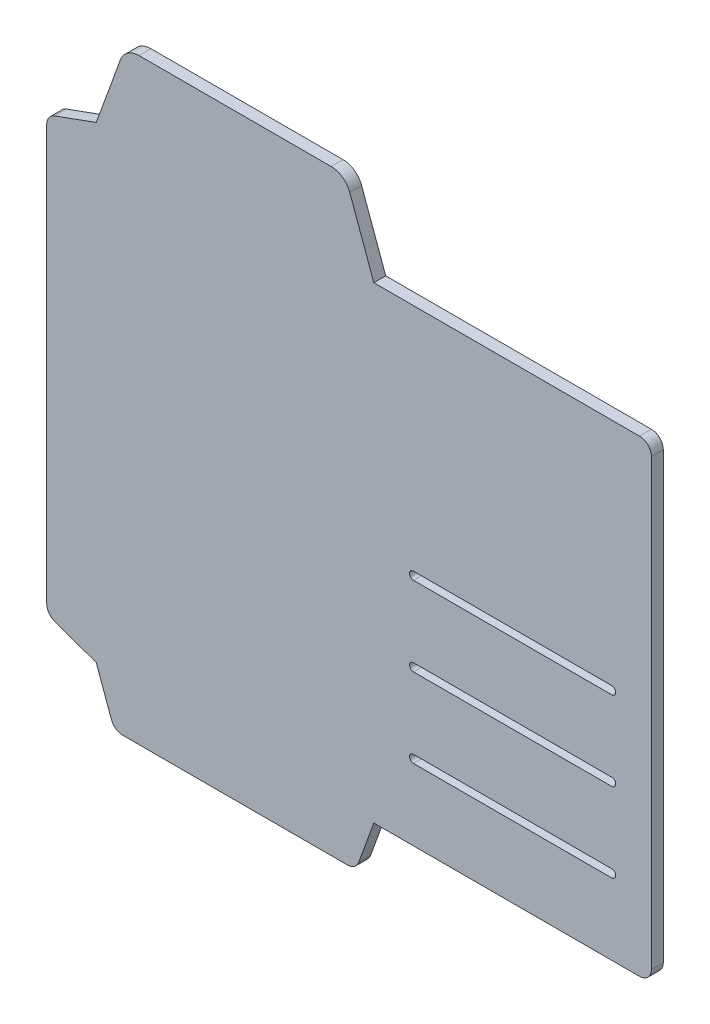
SolidWorks part; units mm, degrees
ref_plane "Front" through (0, 0, 0) normal (0, 0, 1) x (1, 0, 0)
ref_plane "Top" through (0, 0, 0) normal (0, 1, 0) x (1, 0, 0)
ref_plane "Right" through (0, 0, 0) normal (1, 0, 0) x (0, 0, -1)
sketch "Esquisse1" plane through (0, 0, 0) normal (0, 0, 1) x (1, 0, 0)
  line L1 (0, 0) -> (70, 0)
  line L2 (0, 0) -> (0, 118)
  line L3 (0, 118) -> (70, 118)
  line L4 (70, 0) -> (70, 118)
  dimension "D1" = 70
  dimension "D2" = 118
extrude "Boss.-Extru.1" add sketch "Esquisse1" along normal blind 3
sketch "Esquisse2" plane through (0, 0, 3) normal (0, 0, 1) x (1, 0, 0)
  line L0 (0, 0) -> (-12.5, 4.5496)
  line L1 (-12.5, 4.5496) -> (-12.5, 113.4504)
  line L2 (-12.5, 59) -> (0, 59) construction
  line L3 (0, 118) -> (0, 0) construction
  line L4 (0, 118) -> (-12.5, 113.4504)
  line L5 (35, 0) -> (35, -12.5) construction
  line L6 (0, 0) -> (70, 0) construction
  line L7 (65.4504, -12.5) -> (4.5496, -12.5)
  line L8 (4.5496, -12.5) -> (0, 0)
  line L9 (65.4504, -12.5) -> (70, 0)
  line L10 (70, 0) -> (0, 0)
  line L11 (0, 0) -> (0, 118)
  line L12 (70, 118) -> (62.7206, 138)
  line L13 (70, 118) -> (0, 118) construction
  line L14 (70, 0) -> (70, 118) construction
  line L15 (62.7206, 138) -> (7.2794, 138)
  line L16 (35, 138) -> (35, 118) construction
  line L17 (0, 118) -> (7.2794, 138)
  line L18 (0, 118) -> (70, 118)
  line M10 (0, 118) -> (0, 0)
  line M11 (0, 0) -> (70, 0)
  line M13 (70, 118) -> (0, 118)
  dimension "D1" = 12.5
  dimension "D2" = 70
  dimension "D3" = 70
  dimension "D4" = 20
  dimension "D5" = 70
extrude "Boss.-Extru.2" add sketch "Esquisse2" against normal up to vertex (3 mm away) contours L17 L12 L15 M13 | L4 L1 L0 M10 | L7 L9 L8 M11 up to point (70, 118, 0)
fillet "Congé1" radius 3 2 edges at (-12.5, 4.5496, 1.5) (-12.5, 113.4504, 1.5)
fillet "Congé2" radius 3 2 edges at (65.4504, -12.5, 1.5) (4.5496, -12.5, 1.5)
fillet "Congé3" radius 5 2 edges at (7.2794, 138, 1.5) (62.7206, 138, 1.5)
sketch "Esquisse3" plane through (0, 0, 3) normal (0, 0, 1) x (1, 0, 0)
  line L1 (70, 0) -> (140, 0)
  line L2 (70, 0) -> (70, 118)
  line L3 (70, 118) -> (140, 118)
  line L4 (140, 0) -> (140, 118)
  line L5 (70, 0) -> (70, 118) construction
  dimension "D1" = 70
extrude "Boss.-Extru.3" add sketch "Esquisse3" against normal up to vertex (3 mm away)
fillet "Congé4" radius 3 2 edges at (140, 0, 1.5) (140, 118, 1.5)
sketch "Esquisse4" plane through (0, 0, 3) normal (0, 0, 1) x (1, 0, 0)
  line L0 (140, 59) -> (70, 59) construction
  line L1 (140, 3) -> (140, 115) construction
  line L2 (70, 118) -> (70, 59) construction
  line L3 (80, 59) -> (130, 59) construction
  line L4 (80, 60) -> (130, 60)
  line L5 (80, 58) -> (130, 58)
  line L6 (80, 39) -> (130, 39) construction
  line L7 (80, 40) -> (130, 40)
  line L8 (80, 38) -> (130, 38)
  line L9 (80, 19) -> (130, 19) construction
  line L10 (80, 20) -> (130, 20)
  line L11 (80, 18) -> (130, 18)
  line L12 (105, 39) -> (105, 59) construction
  arc A0 (80, 60) -> (80, 58) centre (80, 59) ccw
  arc A1 (130, 58) -> (130, 60) centre (130, 59) ccw
  arc A2 (80, 40) -> (80, 38) centre (80, 39) ccw
  arc A3 (130, 38) -> (130, 40) centre (130, 39) ccw
  arc A4 (80, 20) -> (80, 18) centre (80, 19) ccw
  arc A5 (130, 18) -> (130, 20) centre (130, 19) ccw
  point P8 (105, 59)
  point P17 (105, 39)
  point P24 (105, 19)
  dimension "D1" = 2
  dimension "D2" = 50
  dimension "D4" = 20
  dimension "D3" = 3
extrude "Enlèv. mat.-Extru.1" cut sketch "Esquisse4" against normal through all both and the other way through all
